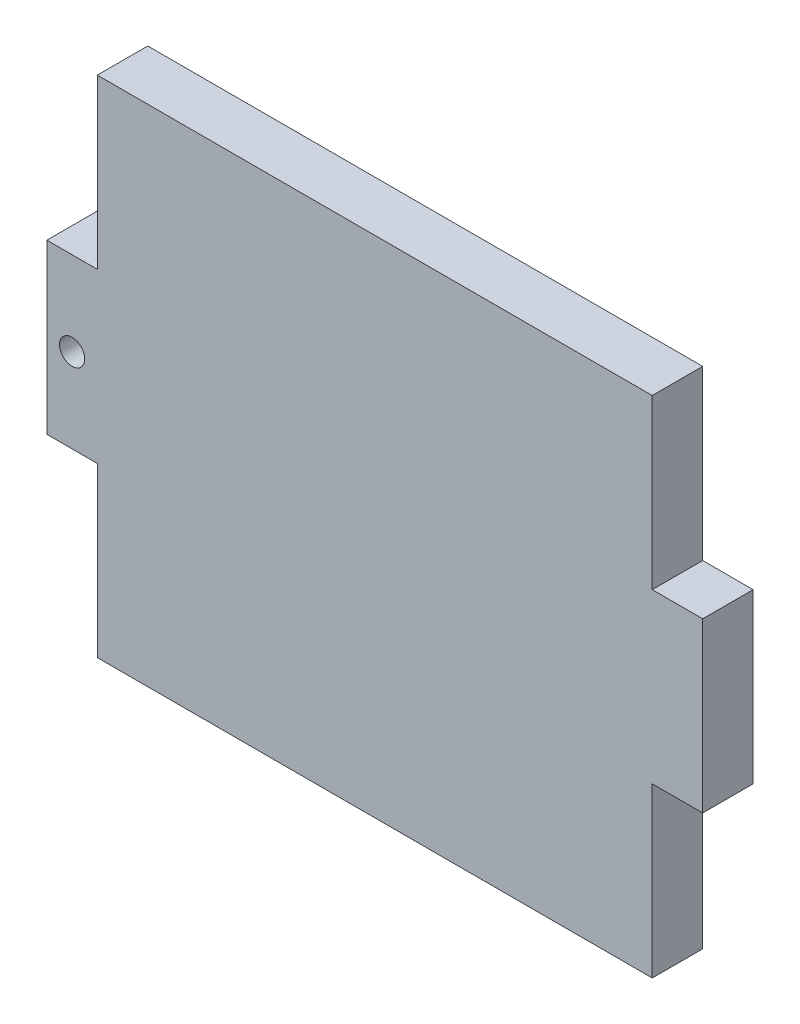
SolidWorks part; units mm, degrees
ref_plane "Plan de face" through (0, 0, 0) normal (0, 0, 1) x (1, 0, 0)
ref_plane "Plan de dessus" through (0, 0, 0) normal (0, 1, 0) x (1, 0, 0)
ref_plane "Plan de droite" through (0, 0, 0) normal (1, 0, 0) x (0, 0, -1)
sketch "Esquisse1" plane through (0, 0, 0) normal (0, 0, 1) x (1, 0, 0)
  line L0 (0, 0) -> (-66, 60) construction
  line L1 (0, 0) -> (-66, 0)
  line L2 (0, 0) -> (0, 20)
  line L3 (0, 60) -> (-66, 60)
  line L4 (-66, 0) -> (-66, 20)
  line L5 (0, 30) -> (6, 30) construction
  line L6 (-66, 0) -> (0, 60) construction
  line L7 (0, 20) -> (6, 20)
  line L9 (0, 40) -> (6, 40)
  line L10 (-66, 40) -> (-72, 40)
  line L11 (-33, 30) -> (-72, 30) construction
  line L12 (-66, 20) -> (-72, 20)
  line L13 (-72, 40) -> (-72, 20)
  line L14 (-66, 40) -> (-66, 60)
  line L15 (-33, 30) -> (0, 30) construction
  line L16 (6, 20) -> (6, 40)
  line L17 (0, 40) -> (0, 60)
  circle A0 centre (-69, 30) radius 1.5
  dimension "D7" = 3
  dimension "D1" = 60
  dimension "D2" = 66
  dimension "D3" = 6
  dimension "D4" = 20
  dimension "D5" = 6
  dimension "D6" = 20
  dimension "D8" = 3
extrude "Boss.-Extru.1" add sketch "Esquisse1" along normal blind 6
